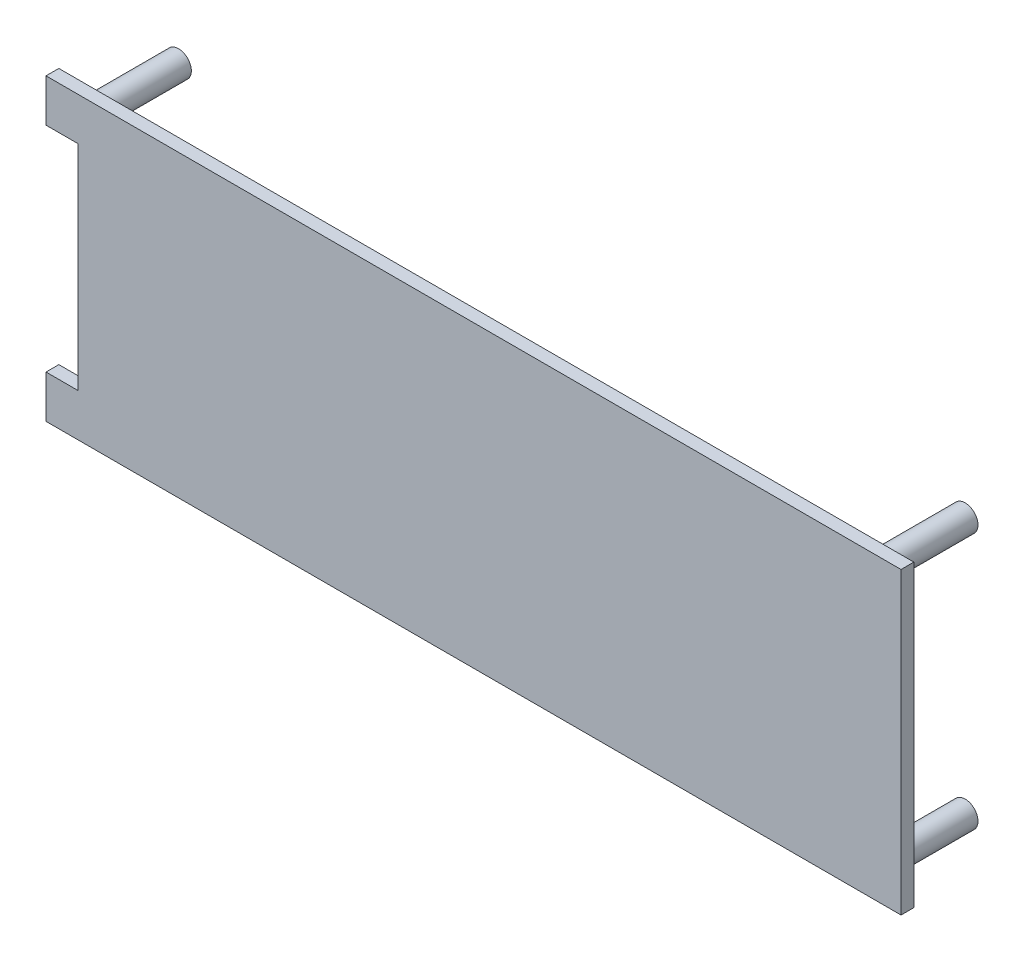
SolidWorks part; units mm, degrees
material "Faia"
ref_plane "Plano frontal" through (0, 0, 0) normal (0, 0, 1) x (1, 0, 0)
ref_plane "Plano superior" through (0, 0, 0) normal (0, 1, 0) x (1, 0, 0)
ref_plane "Plano direito" through (0, 0, 0) normal (1, 0, 0) x (0, 0, -1)
sketch "Esboço2" plane through (0, 0, 0) normal (0, 0, 1) x (1, 0, 0)
  line L0 (200, 34) -> (200, -34) construction
  line L1 (200, -35) -> (0, -35) construction
  line L2 (217.8339, -30) -> (-38.0323, -30) construction
  line L3 (192, -46.6578) -> (192, 65.0673) construction
  line L4 (212.6509, 30) -> (-38.0323, 30) construction
  line L5 (0, 35) -> (200, 35) construction
  line L6 (8, -46.6578) -> (8, 47.0811) construction
  line L7 (0, 34) -> (0, 25) construction
  circle A0 centre (192, -30) radius 3
  circle A1 centre (192, 30) radius 3
  circle A2 centre (8, 30) radius 3
  circle A3 centre (8, -30) radius 3
  dimension "D1" = 8
  dimension "D4" = 8
  dimension "D2" = 5
  dimension "D3" = 5
extrude "Ressalto-extrusão1" add sketch "Esboço2" along normal blind 20
sketch "Esboço3" plane through (0, 0, 20) normal (0, 0, 1) x (1, 0, 0)
  line L1 (0, 35) -> (200, 35)
  line L2 (0, 35) -> (0, -35)
  line L3 (0, -35) -> (200, -35)
  line L4 (200, 35) -> (200, -35)
extrude "Ressalto-extrusão2" add sketch "Esboço3" along normal blind 3
sketch "Esboço4" plane through (0, 0, 23) normal (0, 0, 1) x (1, 0, 0)
  line L0 (200, 35) -> (0, 35) construction
  line L1 (-7.4494, -25) -> (7.4494, -25)
  line L2 (-7.4494, -25) -> (-7.4494, 25)
  line L3 (-7.4494, 25) -> (7.4494, 25)
  line L4 (7.4494, -25) -> (7.4494, 25)
  line L5 (-7.4494, -25) -> (7.4494, 25) construction
  line L6 (-7.4494, 25) -> (7.4494, -25) construction
  point P0 (0, 0)
  dimension "D1" = 10
extrude "Corte-extrusão1" cut sketch "Esboço4" against normal blind 3
